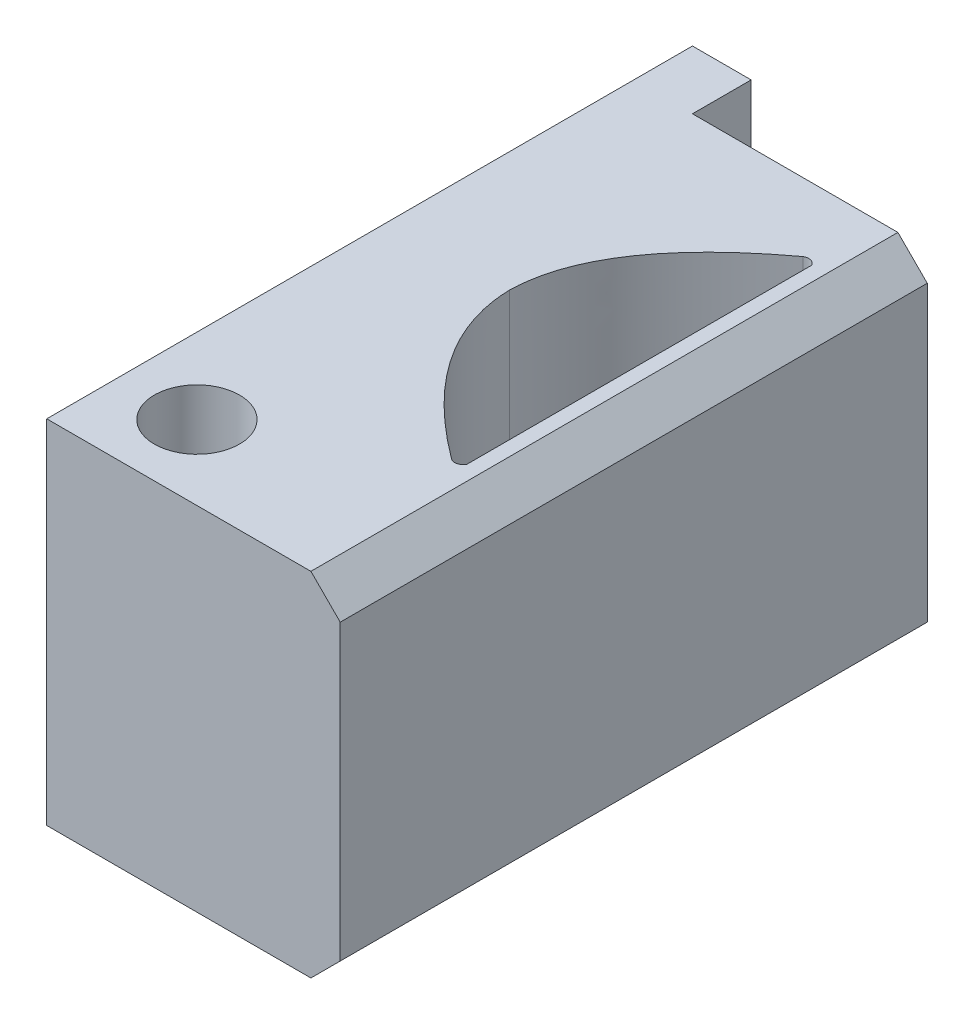
SolidWorks part; units mm, degrees
ref_plane "Front Plane" through (0, 0, 0) normal (0, 0, 1) x (1, 0, 0)
ref_plane "Top Plane" through (0, 0, 0) normal (0, 1, 0) x (1, 0, 0)
ref_plane "Right Plane" through (0, 0, 0) normal (1, 0, 0) x (0, 0, -1)
sketch "Sketch2" plane through (0, 0, 0) normal (0, 1, 0) x (1, 0, 0)
  line L1 (-14.7423, 11.9588) -> (-4.7423, 11.9588)
  line L2 (-14.7423, 11.9588) -> (-14.7423, -8.0412)
  line L3 (-14.7423, -8.0412) -> (-4.7423, -8.0412)
  line L4 (-4.7423, 11.9588) -> (-4.7423, -8.0412)
  dimension "D1" = 20
  dimension "D2" = 10
extrude "Boss-Extrude1" add sketch "Sketch2" along normal up to surface (12 mm away)
sketch "Sketch4" plane through (0, 12, 0) normal (0, 1, 0) x (1, 0, 0)
  circle A0 centre (-12.1614, -5.5054) radius 1.45
  dimension "D1" = 2.9
extrude "Cut-Extrude1" cut sketch "Sketch4" against normal blind 22
sketch "Sketch5" plane through (0, 0, 0) normal (0, -1, 0) x (1, 0, 0)
  line L0 (-6.2423, 2.2313) -> (-6.2423, -9.5198)
  line L1 (-4.7423, 8.0412) -> (-4.7423, -11.9588) construction
  arc A2 (-6.2423, 2.2313) -> (-6.699, 2.3023) centre (-6.4979, 2.0913) ccw
  arc A3 (-6.2423, -9.5198) -> (-6.699, -9.5908) centre (-6.4979, -9.3798) cw
  circle A5 centre (-7.8146, -3.8456) radius 0.2014
  spline S0 degree 3 poles (-6.6425, 2.3444) (-9.1917, 0.4529) (-10.5728, -1.542) (-10.6561, -3.5771) (-10.6574, -3.6442) knots 0.023195 0.023195 0.023195 0.023195 0.477185 0.49267 0.49267 0.49267 0.49267
  spline S1 degree 3 poles (-6.6425, -9.6329) (-9.1917, -7.7414) (-10.5728, -5.7465) (-10.6561, -3.7114) (-10.6574, -3.6442) knots 0.023195 0.023195 0.023195 0.023195 0.477185 0.49267 0.49267 0.49267 0.49267
  dimension "D1" = 1.5
extrude "Cut-Extrude2" cut sketch "Sketch5" against normal blind 34 contours S1 A3 L0 A2 S0 A5 | A5
sketch "Sketch6" plane through (-14.7423, 0, 0) normal (-1, 0, 0) x (0, 0, 1)
  line L0 (8.0412, 6) -> (-8.7559, 6) construction
  line L1 (8.0412, 12) -> (8.0412, 0) construction
  circle A0 centre (-6.9164, 6) radius 4
  dimension "D1" = 8
  dimension "D2" = 0
extrude "Cut-Extrude3" cut sketch "Sketch6" against normal blind 2
sketch "Sketch7" plane through (0, 0, -11.9588) normal (0, 0, -1) x (-1, 0, 0)
  line L6 (4.7423, 12) -> (14.7423, 12) construction
  line L7 (14.7423, 0) -> (12.7423, 0)
  line L8 (14.7423, 0) -> (14.7423, 12)
  line L9 (14.7423, 12) -> (12.7423, 12)
  line L10 (12.7423, 0) -> (12.7423, 12)
  dimension "D1" = 2
extrude "Boss-Extrude4" add sketch "Sketch7" along normal blind 2
chamfer "Chamfer1" distance 1 angle 45 2 edges at (-4.7423, 0, -1.9588) (-4.7423, 12, -1.9588)
